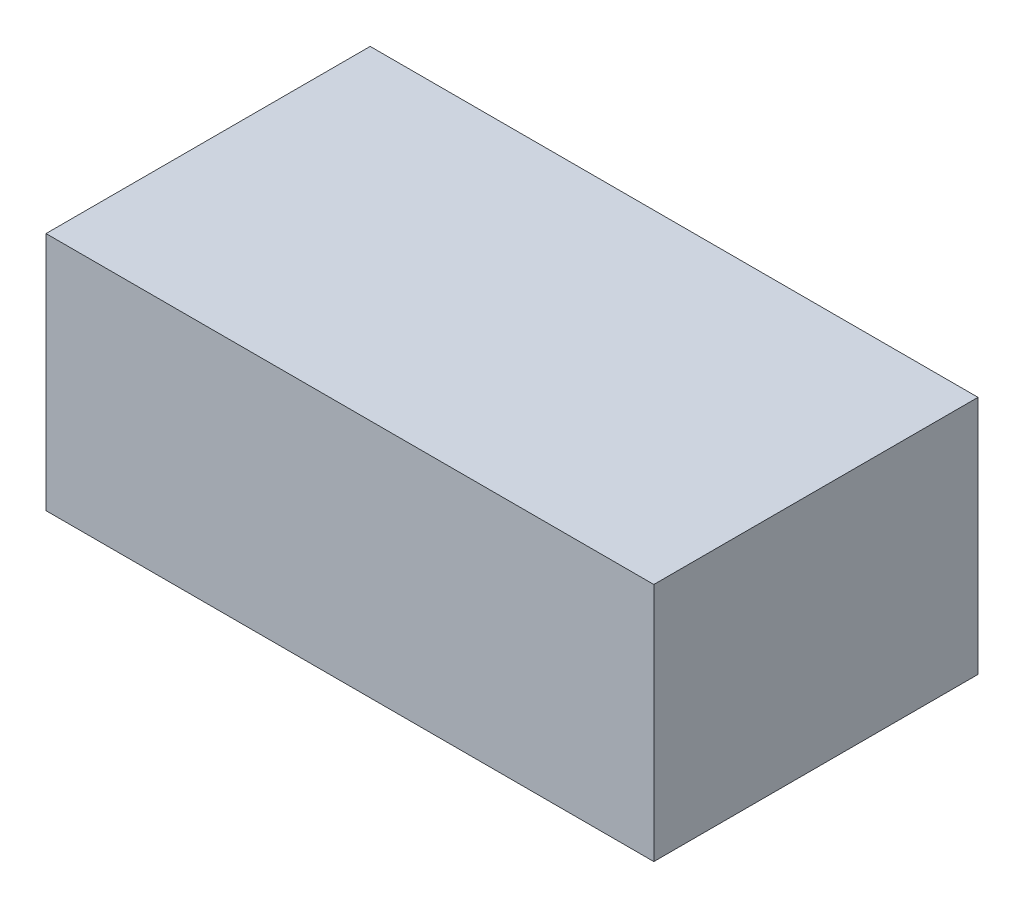
SolidWorks part; units mm, degrees
ref_plane "Спереди" through (0, 0, 0) normal (0, 0, 1) x (1, 0, 0)
ref_plane "Сверху" through (0, 0, 0) normal (0, 1, 0) x (1, 0, 0)
ref_plane "Справа" through (0, 0, 0) normal (1, 0, 0) x (0, 0, -1)
sketch "Эскиз1" plane through (0, 0, 0) normal (0, 1, 0) x (1, 0, 0)
  line L1 (-15, -8) -> (15, -8)
  line L2 (-15, -8) -> (-15, 8)
  line L3 (-15, 8) -> (15, 8)
  line L4 (15, -8) -> (15, 8)
  line L5 (-15, -8) -> (15, 8) construction
  line L6 (-15, 8) -> (15, -8) construction
  point P0 (0, 0)
  dimension "D1" = 30
  dimension "D2" = 16
extrude "Бобышка-Вытянуть1" add sketch "Эскиз1" along normal blind 13
chamfer "Фаска1" distance 2 angle 30 4 edges at (-15, 0, 0) (0, 0, -8) (15, 0, 0) (0, 0, 8)
